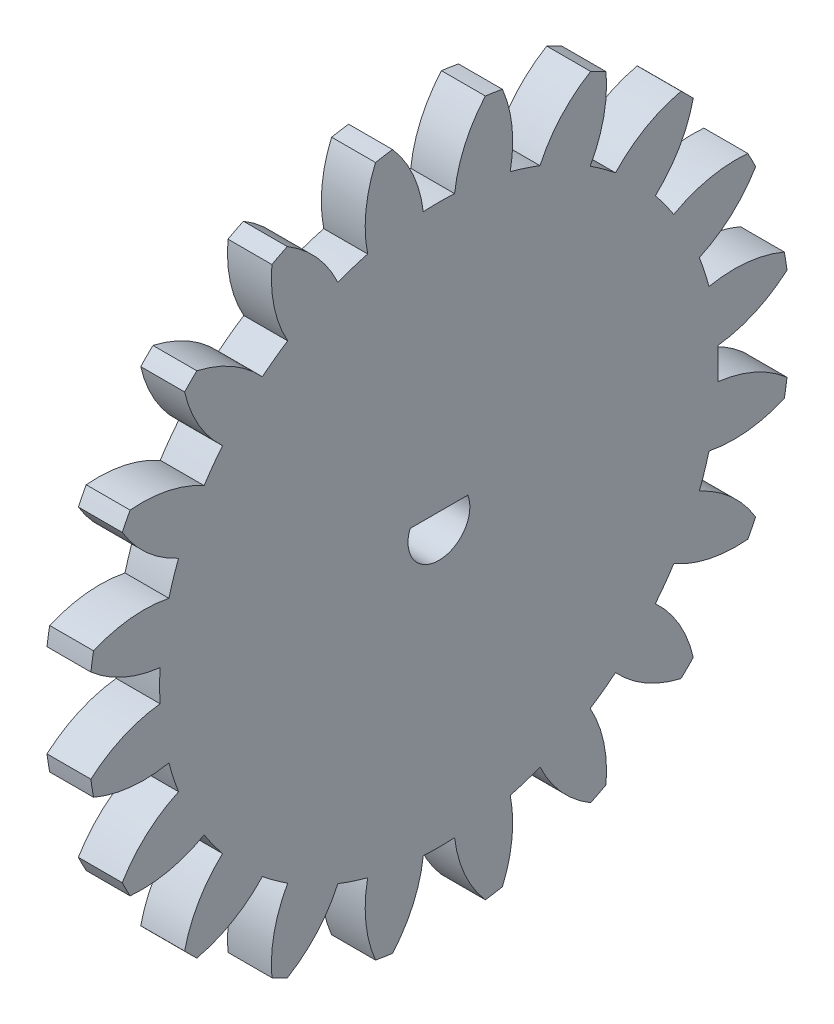
SolidWorks part; units mm, degrees
ref_plane "Plane1" through (0, 0, 0) normal (0, 0, 1) x (1, 0, 0)
ref_plane "Plane2" through (0, 0, 0) normal (0, 1, 0) x (1, 0, 0)
ref_plane "Plane3" through (0, 0, 0) normal (1, 0, 0) x (0, 0, -1)
sketch "HoldingSke" plane through (0, 0, 0) normal (0, 1, 0) x (1, 0, 0)
  line L0 (0, 0) -> (0.2349, -0.0855)
  line L1 (-15, 0) -> (100, 0) construction
  line L2 (0, 0) -> (-2.1039, 2.3779)
  line L3 (0, 0) -> (-11.863, 4.5341)
  line L4 (0, 0) -> (8.1152, 2.9537)
  line L5 (0, 0) -> (-46.8476, -17.4728)
  line L6 (0, 0) -> (-4.5593, -3.0762)
  line L7 (-2.1039, 2.3779) -> (8.6586, 51.2059)
  line L8 (-76.2, 54.61) -> (-76.1, 54.61)
  line L9 (-71.009, 38.7566) -> (-53.1078, 45.2721)
  line L10 (-76.2, 71.12) -> (104.1128, 71.12)
  line L11 (0, 0) -> (-5.5, 0)
  line L12 (-76.2, 101.6) -> (-76.073, 101.6)
  line L13 (24.9733, 27.94) -> (52.9518, 28.4284)
  line L14 (24.9733, 27.94) -> (24.9743, 27.94)
  line L15 (24.9733, 27.94) -> (100.4006, 29.5858)
  line L16 (-63.627, -4) -> (-12.827, -4)
  circle A0 centre (0, 0) radius 0.5
  circle A1 centre (0, 0) radius 34.999
  circle A2 centre (0, 0) radius 37.5
  circle A3 centre (0, 0) radius 0.5
  dimension "MHD" = 69.998
  dimension "Hub_dia" = 75
  dimension "Bore" = 1
  dimension "MBD" = 1
  dimension "Num_teeth" = 20
  dimension "Pitch" = 0.25
  dimension "Overall_len" = 50
  dimension "Show_teeth" = 20
  dimension "Thickness" = 5.5
  dimension "OAL" = 50.0001
  dimension "T_dim" = 0.1
  dimension "Ap" = 20
  dimension "H" = 19.05
  dimension "Pitch_radius" = 180.3128
  dimension "Width" = 5.5
  dimension "Backlash" = 0.127
  dimension "Addendum_fac" = 1
  dimension "Dedendum_fac" = 1.25
  dimension "Clearance_fac" = 0.25
  dimension "Dedendum_add" = 0.001
  dimension "Module" = 4
sketch "BasProSke" plane through (0, 0, 0) normal (0, 1, 0) x (1, 0, 0)
  line L0 (-10, 0) -> (60, 0) construction
  line L1 (0, 0) -> (0, 44)
  line L2 (0, 0) -> (5.5, 0)
  line L3 (5.5, 0) -> (5.5, 44)
  line L4 (5.5, 44) -> (0, 44)
  dimension "Thickness" = 5.5
  dimension "Diameter" = 88
revolve "Base-Revolve" add sketch "BasProSke" angle 360 about L0
sketch "TooCutSke" plane through (0, 0, 0) normal (1, 0, 0) x (0, 0, -1)
  line L1 (0, 0) -> (0, 107) construction
  line L2 (0, 0) -> (-3.3605, 39.8586) construction
  line L3 (0, 0) -> (-12.4815, 78.8048) construction
  line L4 (-3.3605, 39.8586) -> (-6.2407, 39.4024) construction
  arc A0 (1.9617, 34.944) -> (-1.9617, 34.944) centre (0, 0) ccw
  arc A1 (5.8321, 43.6374) -> (-5.8321, 43.6374) centre (0, 0) ccw
  circle A2 centre (0, 0) radius 40 construction
  circle A3 centre (0, 0) radius 37.5877 construction
  arc A4 (-1.9617, 34.944) -> (-5.8321, 43.6374) centre (-17.8525, 33.0775) ccw
  arc A5 (5.8321, 43.6374) -> (1.9617, 34.944) centre (17.8525, 33.0775) ccw
  dimension "Root_dia" = 69.998
  dimension "Overcut_dia" = 88.0508
  dimension "Pitch_dia" = 80
  dimension "Base_dia" = 75.1754
  dimension "Flank_rad" = 16
  dimension "Half_ang" = 9
  dimension "Half_CT" = 2.9161
extrude "ToothCut" cut sketch "TooCutSke" along normal through all
fillet "Breaks" [suppressed] radius 0.08
fillet "RootFillets" [suppressed] radius 1.001
pattern_circular "TeethCuts" count 20 every 18 about axis through (-10, 0, 0) along (1, 0, 0) of "ToothCut", "RootFillets", "Breaks"
sketch "HubNeaOneSke" plane through (0, 0, 0) normal (-1, 0, 0) x (0, 0, 1)
  circle A0 centre (0, 0) radius 34.999
  dimension "Diameter" = 69.998
extrude "HubNearOne" [suppressed] add sketch "HubNeaOneSke" along normal blind 44.5001
sketch "HubNeaBotSke" plane through (0, 0, 0) normal (-1, 0, 0) x (0, 0, 1)
  circle A0 centre (0, 0) radius 34.999
  dimension "Diameter" = 69.998
extrude "HubNearBoth" [suppressed] add sketch "HubNeaBotSke" along normal blind 22.25
ref_plane "FarPln" through (5.5, 0, 0) normal (1, 0, 0) x (0, 0, -1)
sketch "HubFarSke" plane through (5.5, 0, 0) normal (1, 0, 0) x (0, 0, -1)
  circle A0 centre (0, 0) radius 34.999
  dimension "Diameter" = 69.998
extrude "HubFar" [suppressed] add sketch "HubFarSke" along normal blind 22.25
sketch "BorSke" plane through (0, 0, 0) normal (1, 0, 0) x (0, 0, -1)
  circle A0 centre (0, 0) radius 0.5
  dimension "Diameter" = 1
extrude "Bore" cut sketch "BorSke" along normal mid plane 100.0001
sketch "KeySke" plane through (0, 0, 0) normal (1, 0, 0) x (0, 0, -1)
  line L0 (-0.05, 0) -> (-0.05, 0.6)
  line L1 (-0.05, 0.6) -> (0.05, 0.6)
  line L2 (0.05, 0.6) -> (0.05, 0)
  line L3 (0, 0) -> (0, 34) construction
  line L4 (-0.05, 0) -> (0.05, 0)
  dimension "Offset" = 0.6
  dimension "Width" = 0.1
extrude "Keyway" [suppressed] cut sketch "KeySke" along normal mid plane 100.0001
pattern_circular "Keyway2" [suppressed] count 2 every 90 about axis through (-10, 0, 0) along (1, 0, 0)
sketch "Croquis1" plane through (5.5, 0, 0) normal (1, 0, 0) x (0, 0, -1)
  line L1 (0, -3.875) -> (0, 1.395) construction
  line L2 (0, 1.395) -> (3.6152, 1.395)
  line L3 (0, 1.395) -> (-3.6152, 1.395)
  arc A0 (-3.875, 0) -> (3.875, 0) centre (0, 0) ccw
  arc A1 (3.875, 0) -> (3.6152, 1.395) centre (0, 0) ccw
  arc A2 (-3.6152, 1.395) -> (-3.875, 0) centre (0, 0) ccw
  dimension "D1" = 7.75
  dimension "D2" = 5.27
extrude "Cortar-Extruir1" cut sketch "Croquis1" against normal blind 5.5
sketch "Croquis2" plane through (5.5, 0, 0) normal (1, 0, 0) x (0, 0, -1)
  line L0 (-0.5, 0) -> (0.5, 0)
  arc A0 (0.5, 0) -> (-0.5, 0) centre (0, 0) ccw
extrude "Saliente-Extruir1" [suppressed] add sketch "Croquis2" against normal blind 5.5
equation "' \"Module@HoldingSke\" = 6.35"
equation "' \"Num_teeth@HoldingSke\" = 12"
equation "' \"Ap@HoldingSke\" =  20"
equation "' \"Ap@HoldingSke\" = 20"
equation "' \"Width@HoldingSke\" = 0.5 * 25.4"
equation "' \"Hub_dia@HoldingSke\"= 1 * 25.4"
equation "' \"Hub_dia@HoldingSke\" = 1 * 25.4"
equation "' \"Overall_len@HoldingSke\" = 1.0 * 25.4"
equation "' \"Bore@HoldingSke\" = 0.75 * 25.4"
equation "' \"T_dim@HoldingSke\" = 0.1 * 25.4"
equation "' \"Width@KeySke\" = 0.25 * 25.4"
equation "' \"Show_teeth@HoldingSke\" = 13"
equation "' \"Backlash@HoldingSke\" = 0.009 * 25.4"
equation "' \"Addendum_fac@HoldingSke\" = 1.0"
equation "' \"Dedendum_fac@HoldingSke\" = 1.25"
equation "' \"Dedendum_add@HoldingSke\" = 0.00005 * 25.4"
equation "' \"Clearance_fac@HoldingSke\" = 0.25"
equation "\"Pitch@HoldingSke\" = 1 / \"Module@HoldingSke\""
equation "\"Overcut_dia@TooCutSke\" = (\"Num_teeth@HoldingSke\" + 2 * \"Addendum_fac@HoldingSke\") / \"Pitch@HoldingSke\" + 0.002 * 25.4"
equation "\"Pitch_dia@TooCutSke\" = \"Num_teeth@HoldingSke\" / \"Pitch@HoldingSke\""
equation "\"Base_dia@TooCutSke\" = \"Num_teeth@HoldingSke\" / \"Pitch@HoldingSke\" * cos((\"Ap@HoldingSke\"  * 3.14159265 / 180))"
equation "\"Root_dia@TooCutSke\" = (\"Num_teeth@HoldingSke\" + 2) / \"Pitch@HoldingSke\" - 2 * (\"Addendum_fac@HoldingSke\" + \"Dedendum_fac@HoldingSke\") / \"Pitch@HoldingSke\" - \"Dedendum_add@HoldingSke\" * 2"
equation "\"Half_ang@TooCutSke\" = 180 / \"Num_teeth@HoldingSke\""
equation "\"Half_CT@TooCutSke\" = \"Num_teeth@HoldingSke\" / \"Pitch@HoldingSke\" * sin((3.14159265 / 2 / \"Num_teeth@HoldingSke\")) / 2 - 7 * \"Backlash@HoldingSke\" / 4"
equation "\"Flank_rad@TooCutSke\" = \"Num_teeth@HoldingSke\" / \"Pitch@HoldingSke\" / 5"
equation "\"Radius@RootFillets\" = \"Clearance_fac@HoldingSke\" / \"Pitch@HoldingSke\" + \"Dedendum_add@HoldingSke\""
equation "\"Break_rad@Breaks\" = 0.02 / \"Pitch@HoldingSke\""
equation "\"Thickness@HoldingSke\" = \"Width@HoldingSke\""
equation "\"OAL@HoldingSke\" = \"Thickness@HoldingSke\""
equation "\"MHD@HoldingSke\" = (\"Num_teeth@HoldingSke\" + 2) / \"Pitch@HoldingSke\" - 2 * (\"Addendum_fac@HoldingSke\" + \"Dedendum_fac@HoldingSke\")  / \"Pitch@HoldingSke\" - \"Dedendum_add@HoldingSke\" * 2"
equation "\"MBD@HoldingSke\" = (\"Num_teeth@HoldingSke\" + 2) / \"Pitch@HoldingSke\" - 2 * (\"Addendum_fac@HoldingSke\" + \"Dedendum_fac@HoldingSke\")  / \"Pitch@HoldingSke\" - \"Dedendum_add@HoldingSke\" * 2 - 0.002 * 25.4"
equation "\"MHD@HoldingSke\" = ((sgn( \"MHD@HoldingSke\" - \"Hub_dia@HoldingSke\" )-1)*( \"MHD@HoldingSke\" - \"Hub_dia@HoldingSke\" ))/-2+ \"Hub_dia@HoldingSke\""
equation "\"MBD@HoldingSke\" = ((sgn( \"MBD@HoldingSke\" - \"Bore@HoldingSke\" )-1)*( \"MBD@HoldingSke\" - \"Bore@HoldingSke\" ))/-2+ \"Bore@HoldingSke\""
equation "\"OAL@HoldingSke\" = ((sgn( \"OAL@HoldingSke\" - \"Overall_len@HoldingSke\" )+1)*( \"OAL@HoldingSke\" - \"Overall_len@HoldingSke\" ))/2 + \"Overall_len@HoldingSke\" + 0.000002 * 25.4"
equation "\"Num_teeth@TeethCuts\" = int( \"Show_teeth@HoldingSke\" ) + 1"
equation "\"Num_teeth@TeethCuts\" = ((sgn( \"Num_teeth@TeethCuts\" - \"Num_teeth@HoldingSke\" )-1)*( \"Num_teeth@TeethCuts\" - \"Num_teeth@HoldingSke\" ))/-2+ \"Num_teeth@HoldingSke\""
equation "\"Num_teeth@TeethCuts\" = ((sgn( \"Num_teeth@TeethCuts\" - 2.0)+1)*( \"Num_teeth@TeethCuts\" - 2.0))/2 +2.0"
equation "\"Angle@TeethCuts\" = 360.0 / \"Num_teeth@HoldingSke\""
equation "\"Diameter@BasProSke\" = (\"Num_teeth@HoldingSke\" + 2 * \"Addendum_fac@HoldingSke\") / \"Pitch@HoldingSke\""
equation "\"Thickness@BasProSke\"  = \"Thickness@HoldingSke\""
equation "' \"Fillet_rad@BasProSke\" =  \"Thickness@HoldingSke\" * 0.05"
equation "' \"Fillet_rad@BasProSke\" = \"Thickness@HoldingSke\" * 0.05"
equation "\"MHD@HoldingSke\" = ((sgn( \"MHD@HoldingSke\" - \"Root_dia@TooCutSke\" )-1)*( \"MHD@HoldingSke\" - \"Root_dia@TooCutSke\" ))/-2+ \"Root_dia@TooCutSke\""
equation "\"Diameter@HubNeaOneSke\" = \"MHD@HoldingSke\""
equation "\"Length@HubNearOne\" = \"OAL@HoldingSke\" - \"Thickness@BasProSke\""
equation "\"Diameter@HubNeaBotSke\" = \"MHD@HoldingSke\""
equation "\"Length@HubNearBoth\" = ( \"OAL@HoldingSke\" - \"Thickness@BasProSke\" ) / 2.0"
equation "\"Thickness@FarPln\" = \"Thickness@BasProSke\""
equation "\"Diameter@HubFarSke\" = \"MHD@HoldingSke\""
equation "\"Length@HubFar\" = ( \"OAL@HoldingSke\" - \"Thickness@BasProSke\" ) / 2.0"
equation "\"Diameter@BorSke\" = \"MBD@HoldingSke\""
equation "\"D1@Bore\" = \"OAL@HoldingSke\" * 2.0"
equation "\"D1@Keyway\" = \"OAL@HoldingSke\" * 2.0"
equation "\"Offset@KeySke\" = \"T_dim@HoldingSke\" + \"MBD@HoldingSke\" / 2.0"
